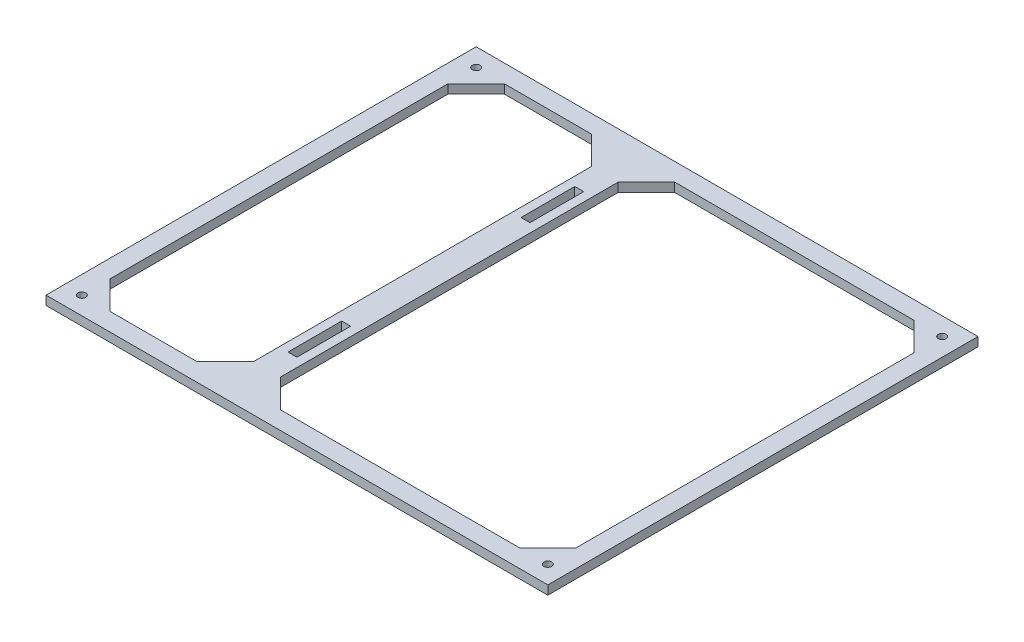
SolidWorks part; units mm, degrees
ref_plane "Front Plane" through (0, 0, 0) normal (0, 0, 1) x (1, 0, 0)
ref_plane "Top Plane" through (0, 0, 0) normal (0, 1, 0) x (1, 0, 0)
ref_plane "Right Plane" through (0, 0, 0) normal (1, 0, 0) x (0, 0, -1)
sketch "Sketch1" plane through (0, 0, 0) normal (0, 1, 0) x (1, 0, 0)
  line L0 (6.35, 16.35) -> (16.35, 6.35)
  line L2 (0, 0) -> (177.8, 0)
  line L3 (0, 0) -> (0, 152.4)
  line L4 (0, 152.4) -> (177.8, 152.4)
  line L5 (16.35, 146.05) -> (47.15, 146.05)
  line L6 (6.35, 136.05) -> (6.35, 16.35)
  line L7 (16.35, 6.35) -> (47.15, 6.35)
  line L8 (57.15, 136.05) -> (57.15, 16.35)
  line L9 (76.675, 146.05) -> (161.45, 146.05)
  line L10 (66.675, 136.05) -> (66.675, 16.35)
  line L11 (76.675, 6.35) -> (161.45, 6.35)
  line L12 (171.45, 136.05) -> (171.45, 16.35)
  line L13 (6.35, 136.05) -> (16.35, 146.05)
  line L14 (47.15, 146.05) -> (57.15, 136.05)
  line L15 (47.15, 6.35) -> (57.15, 16.35)
  line L16 (66.675, 16.35) -> (76.675, 6.35)
  line L17 (66.675, 136.05) -> (76.675, 146.05)
  line L18 (161.45, 146.05) -> (171.45, 136.05)
  line L19 (161.45, 6.35) -> (171.45, 16.35)
  line L20 (177.8, 0) -> (177.8, 152.4)
  line L21 (60.325, 127) -> (63.5, 127)
  line L22 (60.325, 127) -> (60.325, 107.95)
  line L23 (60.325, 107.95) -> (63.5, 107.95)
  line L24 (63.5, 127) -> (63.5, 107.95)
  line L25 (60.325, 25.4) -> (63.5, 25.4)
  line L26 (60.325, 25.4) -> (60.325, 44.45)
  line L27 (60.325, 44.45) -> (63.5, 44.45)
  line L28 (63.5, 25.4) -> (63.5, 44.45)
  circle A0 centre (6.35, 146.05) radius 1.375
  circle A3 centre (6.35, 6.35) radius 1.375
  circle A4 centre (171.45, 6.35) radius 1.375
  circle A5 centre (171.45, 146.05) radius 1.375
  point P5 (6.35, 146.05)
  point P6 (57.15, 6.35)
  point P7 (6.35, 6.35)
  point P8 (57.15, 146.05)
  point P9 (66.675, 146.05)
  point P10 (171.45, 6.35)
  point P11 (66.675, 6.35)
  point P12 (171.45, 146.05)
  point P34 (66.675, 146.05)
  point P37 (6.35, 6.35)
  point P40 (171.45, 6.35)
  point P43 (171.45, 146.05)
  point P46 (57.15, 6.35)
  dimension "D11" = 2.75
  dimension "D10" = 2.75
  dimension "D12" = 2.75
  dimension "D21" = 2.75
  dimension "D3" = 139.7
  dimension "D4" = 152.4
  dimension "D5" = 139.7
  dimension "D6" = 177.8
  dimension "D7" = 50.8
  dimension "D8" = 6.35
  dimension "D9" = 9.525
  dimension "D22" = 3.175
  dimension "D23" = 3.175
  dimension "D24" = 19.05
  dimension "D25" = 25.4
  dimension "D26" = 19.05
  dimension "D27" = 3.175
  dimension "D28" = 25.4
extrude "Boss-Extrude5" add sketch "Sketch1" along normal blind 3.175 contours L14 L8 L15 L7 L0 L6 L13 L5
